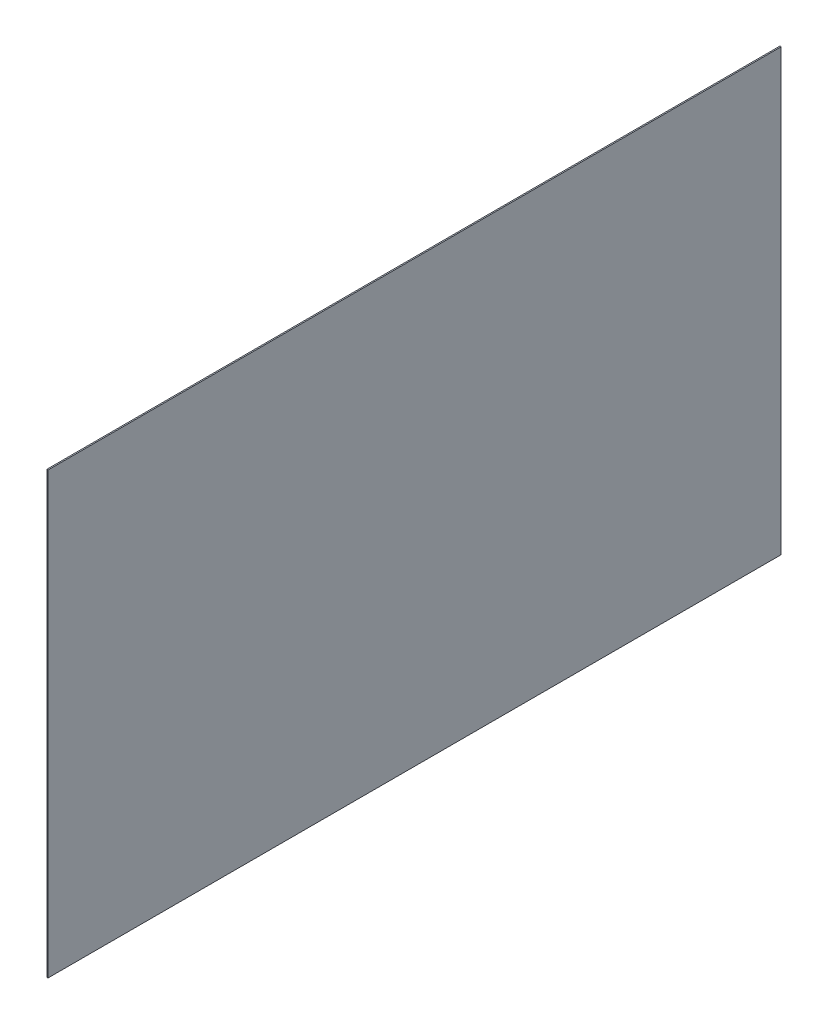
SolidWorks part; units mm, degrees
material "ABS"
ref_plane "Front Plane" through (0, 0, 0) normal (0, 0, 1) x (1, 0, 0)
ref_plane "Top Plane" through (0, 0, 0) normal (0, 1, 0) x (1, 0, 0)
ref_plane "Right Plane" through (0, 0, 0) normal (1, 0, 0) x (0, 0, -1)
sketch "Sketch1" plane through (0, 0, 0) normal (1, 0, 0) x (0, 0, -1)
  line L1 (-762, -457.2) -> (762, -457.2)
  line L2 (-762, -457.2) -> (-762, 457.2)
  line L3 (-762, 457.2) -> (762, 457.2)
  line L4 (762, -457.2) -> (762, 457.2)
  line L5 (-762, -457.2) -> (762, 457.2) construction
  line L6 (-762, 457.2) -> (762, -457.2) construction
  point P0 (0, 0)
  dimension "D1" = 914.4
  dimension "D2" = 1524
extrude "Boss-Extrude1" add sketch "Sketch1" along normal blind 2.54
equation "\"D1@Sketch1\"=3ft"
equation "\"D2@Sketch1\"=5ft"
